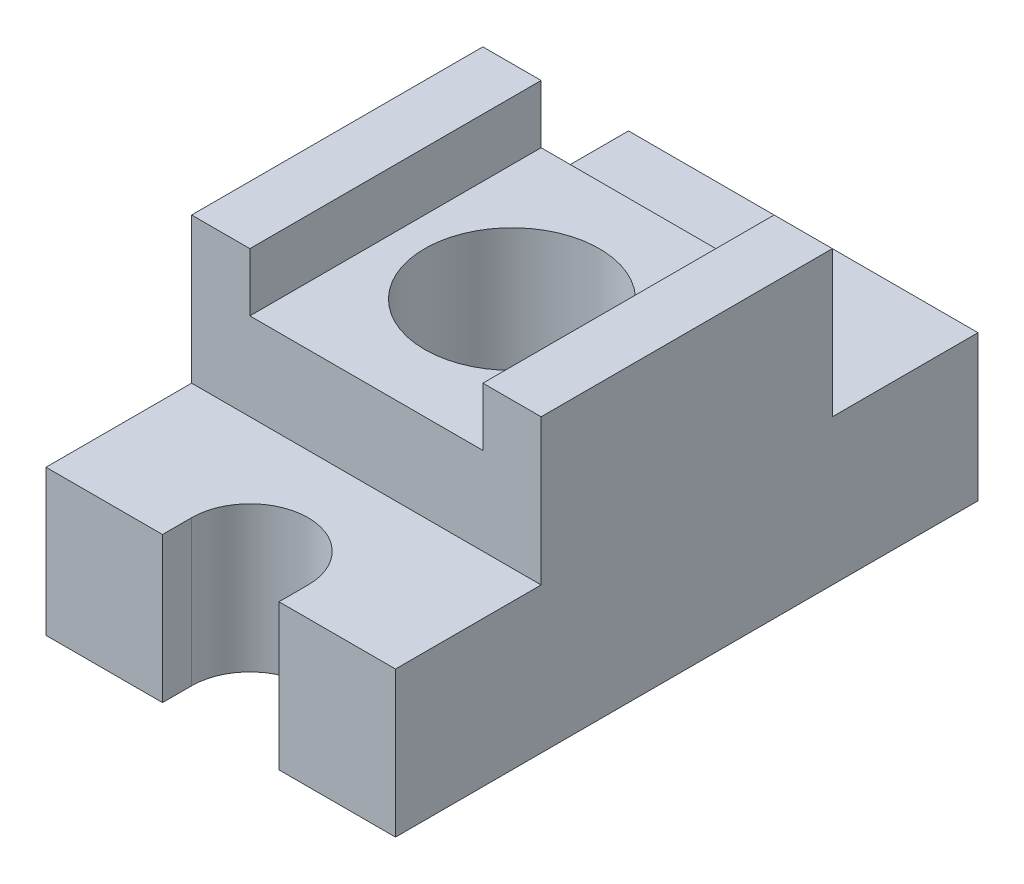
SolidWorks part; units mm, degrees
ref_plane "Plan de face" through (0, 0, 0) normal (0, 0, 1) x (1, 0, 0)
ref_plane "Plan de dessus" through (0, 0, 0) normal (0, 1, 0) x (1, 0, 0)
ref_plane "Plan de droite" through (0, 0, 0) normal (1, 0, 0) x (0, 0, -1)
sketch "Esquisse1" plane through (0, 0, 0) normal (1, 0, 0) x (0, 0, -1)
  line L0 (-50, 0) -> (-25, 0)
  line L1 (-50, -25) -> (50, -25)
  line L2 (-50, -25) -> (-50, 0)
  line L3 (-25, 25) -> (25, 25)
  line L4 (50, -25) -> (50, 0)
  line L5 (-50, -25) -> (25, 12.5) construction
  line L6 (-25, 12.5) -> (50, -25) construction
  line L7 (-25, 0) -> (-25, 25)
  line L8 (50, 0) -> (25, 0)
  line L9 (25, 0) -> (25, 25)
  point P0 (0, 0)
  dimension "D1" = 25
  dimension "D2" = 50
  dimension "D3" = 50
  dimension "D4" = 100
  dimension "D5" = 50
  dimension "D6" = 25
extrude "Boss.-Extru.1" add sketch "Esquisse1" along normal blind 60 contours L0 L7 L3 L9 L8 L4 L1 L2
sketch "Esquisse2" plane through (0, 0, 0) normal (0, 1, 0) x (1, 0, 0)
  line L0 (30, -45) -> (30, -60) construction
  line L1 (40, -45) -> (40, -60)
  line L2 (20, -45) -> (20, -60)
  line L3 (0, -50) -> (0, -25) construction
  line L4 (60, -50) -> (0, -50) construction
  arc A0 (40, -45) -> (20, -45) centre (30, -45) ccw
  arc A1 (20, -60) -> (40, -60) centre (30, -60) ccw
  point P2 (30, -52.5)
  point P9 (0, 0)
  point P14 (30, -55)
  dimension "D2" = 10
  dimension "D1" = 5
  dimension "D3" = 30
  dimension "D4" = 15
extrude "Enlèv. mat.-Extru.1" cut sketch "Esquisse2" against normal through all
sketch "Esquisse3" plane through (0, 25, 0) normal (0, 1, 0) x (1, 0, 0)
  line L0 (60, 25) -> (0, 25) construction
  line L1 (10, -25) -> (50, -25)
  line L2 (10, -25) -> (10, 25)
  line L3 (10, 25) -> (50, 25)
  line L4 (50, -25) -> (50, 25)
  line L5 (10, -25) -> (50, 25) construction
  line L6 (10, 25) -> (50, -25) construction
  line L7 (60, -25) -> (60, 25) construction
  point P0 (30, 0)
  dimension "D1" = 40
  dimension "D2" = 10
  dimension "D3" = 50
extrude "Enlèv. mat.-Extru.2" cut sketch "Esquisse3" against normal blind 10
sketch "Esquisse4" plane through (0, 15, 0) normal (0, 1, 0) x (1, 0, 0)
  line L0 (10, -25) -> (50, -25) construction
  line L1 (50, -25) -> (50, 25) construction
  circle A0 centre (30, 0) radius 15
  dimension "D1" = 30
  dimension "D2" = 25
  dimension "D3" = 20
extrude "Enlèv. mat.-Extru.3" cut sketch "Esquisse4" against normal through all contours A0
